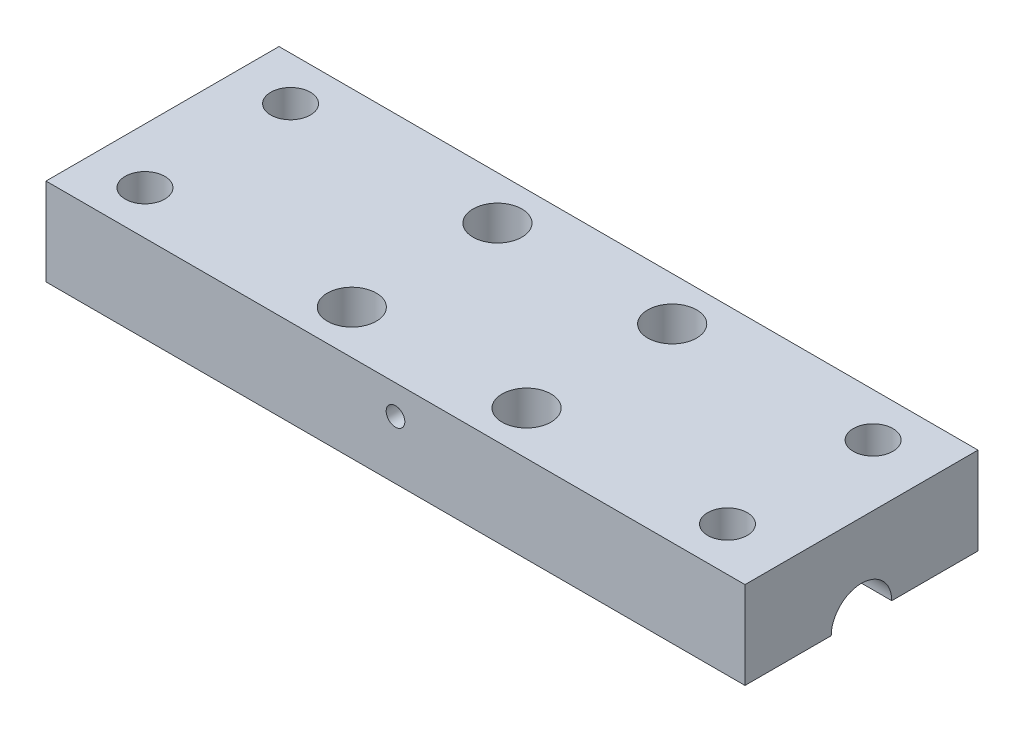
SolidWorks part; units mm, degrees
ref_plane "Front Plane" through (0, 0, 0) normal (0, 0, 1) x (1, 0, 0)
ref_plane "Top Plane" through (0, 0, 0) normal (0, 1, 0) x (1, 0, 0)
ref_plane "Right Plane" through (0, 0, 0) normal (1, 0, 0) x (0, 0, -1)
sketch "Sketch1" plane through (0, 0, 0) normal (0, 1, 0) x (1, 0, 0)
  line L1 (-38.1, 12.7) -> (38.1, 12.7)
  line L2 (-38.1, 12.7) -> (-38.1, -12.7)
  line L3 (-38.1, -12.7) -> (38.1, -12.7)
  line L4 (38.1, 12.7) -> (38.1, -12.7)
  dimension "D1" = 25.4
  dimension "D2" = 76.2
  dimension "D3" = 38.1
  dimension "D4" = 12.7
extrude "Boss-Extrude1" add sketch "Sketch1" along normal blind 9.525
sketch "Sketch2" plane through (0, 9.525, 0) normal (0, 1, 0) x (1, 0, 0)
  circle A0 centre (-32.0741, 7.9375) radius 2.159
  circle A1 centre (-32.0741, -7.9375) radius 2.159
  circle A2 centre (31.4259, 7.9375) radius 2.159
  circle A3 centre (31.4259, -7.9375) radius 2.159
  dimension "D1" = 4.318
  dimension "D2" = 15.875
  dimension "D3" = 63.5
  dimension "D4" = 32.0741
  dimension "D5" = 7.9375
extrude "Cut-Extrude1" cut sketch "Sketch2" against normal through all
sketch "Sketch3" plane through (0, 9.525, 0) normal (0, 1, 0) x (1, 0, 0)
  circle A0 centre (-9.525, 7.9375) radius 2.667
  circle A1 centre (-9.525, -7.9375) radius 2.667
  circle A2 centre (9.525, 7.9375) radius 2.667
  circle A3 centre (9.525, -7.9375) radius 2.667
  dimension "D1" = 5.334
  dimension "D2" = 15.875
  dimension "D3" = 19.05
  dimension "D4" = 7.9375
  dimension "D5" = 9.525
extrude "Cut-Extrude2" cut sketch "Sketch3" against normal through all
sketch "Sketch4" plane through (0, 0, 12.7) normal (0, 0, 1) x (1, 0, 0)
  line L0 (-38.1, 9.525) -> (-38.1, 0) construction
  circle A0 centre (0, 6.35) radius 1.016
  dimension "D1" = 2.032
  dimension "D2" = 6.35
  dimension "D3" = 38.1
extrude "Cut-Extrude3" cut sketch "Sketch4" against normal blind 7.62
sketch "Sketch5" plane through (0, 0, -12.7) normal (0, 0, -1) x (-1, 0, 0)
  line L0 (-38.1, 9.525) -> (-38.1, 0) construction
  circle A0 centre (0, 6.35) radius 1.016
  dimension "D3" = 2.032
  dimension "D1" = 6.35
  dimension "D2" = 38.1
extrude "Cut-Extrude4" cut sketch "Sketch5" against normal blind 7.62
sketch "Sketch7" plane through (38.1, 0, 0) normal (1, 0, 0) x (0, 0, -1)
  circle A0 centre (0, 0) radius 3.302
  dimension "D1" = 6.604
extrude "Cut-Extrude5" cut sketch "Sketch7" against normal through all
